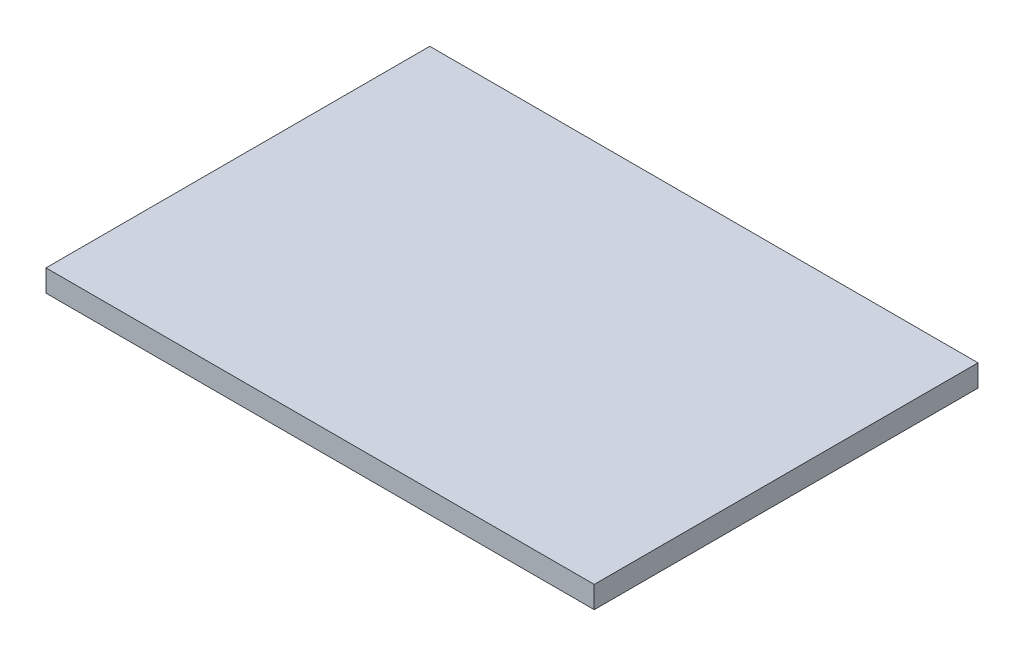
SolidWorks part; units mm, degrees
ref_plane "Front Plane" through (0, 0, 0) normal (0, 0, 1) x (1, 0, 0)
ref_plane "Top Plane" through (0, 0, 0) normal (0, 1, 0) x (1, 0, 0)
ref_plane "Right Plane" through (0, 0, 0) normal (1, 0, 0) x (0, 0, -1)
sketch "Sketch1" plane through (0, 0, 0) normal (0, 1, 0) x (1, 0, 0)
  line L1 (-25, -17.5) -> (25, -17.5)
  line L2 (-25, -17.5) -> (-25, 17.5)
  line L3 (-25, 17.5) -> (25, 17.5)
  line L4 (25, -17.5) -> (25, 17.5)
  line L5 (-25, -17.5) -> (25, 17.5) construction
  line L6 (-25, 17.5) -> (25, -17.5) construction
  point P0 (0, 0)
  dimension "D1" = 35
  dimension "D2" = 50
extrude "Boss-Extrude1" add sketch "Sketch1" along normal blind 2
